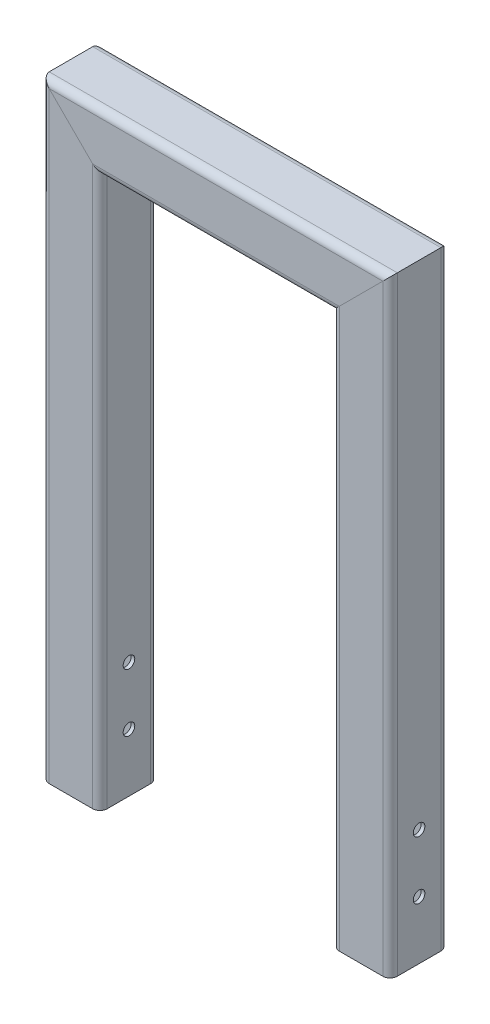
SolidWorks part; units mm, degrees
material "Chrome Stainless Steel"
ref_plane "Front Plane" through (0, 0, 0) normal (0, 0, 1) x (1, 0, 0)
ref_plane "Top Plane" through (0, 0, 0) normal (0, 1, 0) x (1, 0, 0)
ref_plane "Right Plane" through (0, 0, 0) normal (1, 0, 0) x (0, 0, -1)
sketch3d "3DSketch1"
  line L0 (0, 0, 0) -> (0, 800, 0)
  line L5 (0, 800, 0) -> (400, 800, 0)
  line L6 (400, 800, 0) -> (400, 0, 0)
  dimension "D1" = 800
  dimension "D2" = 400
  dimension "D3" = 800
other "Square tube 80 X 80 X 5(1)"
ref_plane "Plane3" through (0, 0, 0) normal (0, 1, 0) x (1, 0, 0)
sketch "Sketch1" plane through (0, 0, 0) normal (0, 1, 0) x (1, 0, 0)
  line L0 (-30, -35) -> (30, -35)
  line L1 (-35, -30) -> (-35, 30)
  line L2 (30, 35) -> (-30, 35)
  line L3 (35, 30) -> (35, -30)
  line L4 (-30, -40) -> (30, -40)
  line L5 (-40, -30) -> (-40, 30)
  line L6 (30, 40) -> (-30, 40)
  line L7 (40, 30) -> (40, -30)
  arc A0 (40, 30) -> (30, 40) centre (30, 30) ccw
  arc A1 (30, -40) -> (40, -30) centre (30, -30) ccw
  arc A2 (-40, -30) -> (-30, -40) centre (-30, -30) ccw
  arc A3 (-30, 40) -> (-40, 30) centre (-30, 30) ccw
  arc A4 (-30, 35) -> (-35, 30) centre (-30, 30) ccw
  arc A5 (35, 30) -> (30, 35) centre (30, 30) ccw
  arc A6 (30, -35) -> (35, -30) centre (30, -30) ccw
  arc A7 (-35, -30) -> (-30, -35) centre (-30, -30) ccw
  point P0 (-40, 0)
  point P1 (40, 0)
  point P2 (0, 40)
  point P3 (0, -40)
  point P4 (0, 0)
  point P5 (-40, -40)
  point P6 (40, -40)
  point P7 (40, 40)
  point P8 (-40, 40)
  point P33 (0, 0)
  dimension "D1" = 10
  dimension "Thickness" = 5
  dimension "V_leg" = 80
sketch "Sketch112" plane through (440, 0, 0) normal (1, 0, 0) x (0, 0, -1)
  line L0 (0, -20.4097) -> (0, 1285.9562) construction
  line L1 (30, 0) -> (-30, 0) construction
  circle A0 centre (0, 160) radius 8
  circle A1 centre (0, 80) radius 8
  dimension "D1" = 16
  dimension "D2" = 16
  dimension "D3" = 80
  dimension "D4" = 80
extrude "Cut-Extrude1" cut sketch "Sketch112" against normal up to surface (480 mm away)
